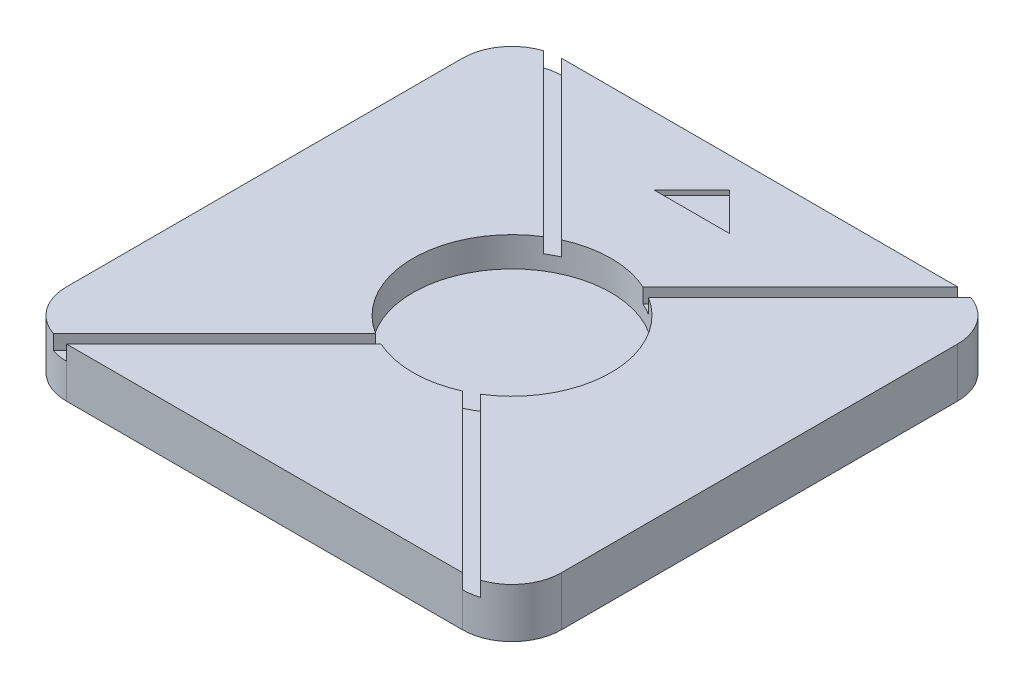
SolidWorks part; units mm, degrees
ref_plane "前视基准面" through (0, 0, 0) normal (0, 0, 1) x (1, 0, 0)
ref_plane "上视基准面" through (0, 0, 0) normal (0, 1, 0) x (1, 0, 0)
ref_plane "右视基准面" through (0, 0, 0) normal (1, 0, 0) x (0, 0, -1)
sketch "草图1" plane through (0, 0, 0) normal (0, 1, 0) x (1, 0, 0)
  line L1 (-61.5517, 50) -> (18.4483, 50)
  line L2 (-71.5517, 40) -> (-71.5517, -40)
  line L3 (-61.5517, -50) -> (18.4483, -50)
  line L4 (28.4483, 40) -> (28.4483, -40)
  arc A0 (-61.5517, -50) -> (-71.5517, -40) centre (-61.5517, -40) cw
  arc A1 (18.4483, -50) -> (28.4483, -40) centre (18.4483, -40) ccw
  arc A2 (28.4483, 40) -> (18.4483, 50) centre (18.4483, 40) ccw
  arc A3 (-61.5517, 50) -> (-71.5517, 40) centre (-61.5517, 40) ccw
  point P6 (-71.5517, -50)
  point P11 (28.4483, 50)
  point P14 (-71.5517, 50)
  dimension "D3" = 10
  dimension "D1" = 100
  dimension "D2" = 100
extrude "凸台-拉伸1" add sketch "草图1" along normal blind 10
sketch "草图2" plane through (0, 10, 0) normal (0, 1, 0) x (1, 0, 0)
  line L0 (-21.5517, 50) -> (-21.5517, -50) construction
  line L1 (18.4483, 50) -> (-61.5517, 50) construction
  line L2 (-61.5517, -50) -> (18.4483, -50) construction
  line L3 (-71.5517, 0) -> (28.4483, 0) construction
  line L4 (-71.5517, 40) -> (-71.5517, -40) construction
  line L5 (28.4483, -40) -> (28.4483, 40) construction
  line L6 (-61.5517, 50) -> (-21.5517, 10)
  line L7 (-21.5517, 10) -> (18.4483, 50)
  line L8 (-21.5517, 6.323) -> (-64.7151, 49.4865)
  line L9 (-21.5517, 6.323) -> (21.6117, 49.4865)
  line L10 (18.4483, -50) -> (-21.5517, -10)
  line L11 (-21.5517, -10) -> (-61.5517, -50)
  line L12 (-64.7151, -49.4865) -> (-21.5517, -6.323)
  line L13 (-21.5517, -6.323) -> (21.6117, -49.4865)
  arc A0 (-61.5517, 50) -> (-71.5517, 40) centre (-61.5517, 40) ccw construction
  arc A1 (28.4483, 40) -> (18.4483, 50) centre (18.4483, 40) ccw construction
  arc A2 (-71.5517, -40) -> (-61.5517, -50) centre (-61.5517, -40) ccw construction
  arc A3 (18.4483, -50) -> (28.4483, -40) centre (18.4483, -40) ccw construction
  arc A4 (-61.5517, 50) -> (-64.7151, 49.4865) centre (-61.5517, 40) ccw
  arc A6 (18.4483, 50) -> (21.6117, 49.4865) centre (18.4483, 40) cw
  arc A7 (-61.5517, -50) -> (-64.7151, -49.4865) centre (-61.5517, -40) cw
  arc A8 (18.4483, -50) -> (21.6117, -49.4865) centre (18.4483, -40) ccw
  arc M11 (-71.5517, -40) -> (-61.5517, -50) centre (-61.5517, -40) ccw
  arc M13 (18.4483, -50) -> (28.4483, -40) centre (18.4483, -40) ccw
  arc M15 (28.4483, 40) -> (18.4483, 50) centre (18.4483, 40) ccw
  arc M17 (-61.5517, 50) -> (-71.5517, 40) centre (-61.5517, 40) ccw
  dimension "D1" = 2.6
  dimension "D2" = 2.6
extrude "切除-拉伸1" cut sketch "草图2" against normal blind 3 contours L8 L9 L7 L6 M15 M17 | L13 L12 L11 L10 M11 M13
sketch "草图3" plane through (0, 10, 0) normal (0, 1, 0) x (1, 0, 0)
  line L0 (-21.5517, 6.323) -> (-21.5517, -6.323) construction
  circle A0 centre (-21.5517, 0) radius 20
  point P4 (-21.5517, 0)
extrude "切除-拉伸2" cut sketch "草图3" against normal blind 6
sketch "草图5" plane through (0, 10, 0) normal (0, 1, 0) x (1, 0, 0)
  line L0 (-21.5517, 43.9409) -> (-29.1901, 36.3026)
  line L1 (-29.1901, 36.3026) -> (-13.9134, 36.3026)
  line L2 (-13.9134, 36.3026) -> (-21.5517, 43.9409)
  line L3 (18.4483, 50) -> (-61.5517, 50) construction
  point P4 (-21.5517, 50)
extrude "切除-拉伸3" cut sketch "草图5" against normal blind 1
